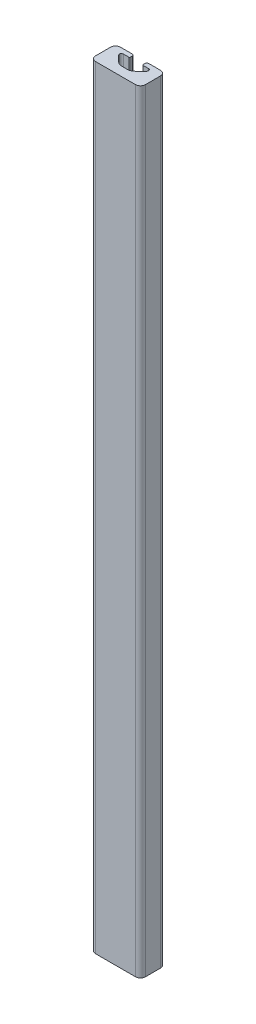
SolidWorks part; units mm, degrees
ref_plane "Alzado" through (0, 0, 0) normal (0, 0, 1) x (1, 0, 0)
ref_plane "Planta" through (0, 0, 0) normal (0, 1, 0) x (1, 0, 0)
ref_plane "Vista lateral" through (0, 0, 0) normal (1, 0, 0) x (0, 0, -1)
sketch "Croquis1" plane through (0, 0, 0) normal (0, 1, 0) x (1, 0, 0)
  line L0 (4.625, 10) -> (0, 10)
  line L1 (-2, 8) -> (-2, 2)
  line L2 (0, 0) -> (16, 0)
  line L3 (18, 2) -> (18, 8)
  line L4 (16, 10) -> (11.375, 10)
  line L5 (10.575, 9.2) -> (10.575, 8.5)
  line L6 (10.875, 8.2) -> (13.0441, 8.2)
  line L7 (13.5957, 6.8685) -> (11.2559, 4.5287)
  line L8 (9.1346, 3.65) -> (6.8654, 3.65)
  line L9 (4.7441, 4.5287) -> (2.4043, 6.8685)
  line L10 (2.9559, 8.2) -> (5.125, 8.2)
  line L11 (5.425, 8.5) -> (5.425, 9.2)
  arc A0 (0, 10) -> (-2, 8) centre (0, 8) ccw
  arc A1 (-2, 2) -> (0, 0) centre (0, 2) ccw
  arc A2 (16, 0) -> (18, 2) centre (16, 2) ccw
  arc A3 (18, 8) -> (16, 10) centre (16, 8) ccw
  arc A4 (11.375, 10) -> (10.575, 9.2) centre (11.375, 9.2) ccw
  arc A5 (10.575, 8.5) -> (10.875, 8.2) centre (10.875, 8.5) ccw
  arc A6 (13.5957, 6.8685) -> (13.0441, 8.2) centre (13.0441, 7.42) ccw
  arc A7 (9.1346, 3.65) -> (11.2559, 4.5287) centre (9.1346, 6.65) ccw
  arc A8 (4.7441, 4.5287) -> (6.8654, 3.65) centre (6.8654, 6.65) ccw
  arc A9 (2.9559, 8.2) -> (2.4043, 6.8685) centre (2.9559, 7.42) ccw
  arc A10 (5.125, 8.2) -> (5.425, 8.5) centre (5.125, 8.5) ccw
  arc A11 (5.425, 9.2) -> (4.625, 10) centre (4.625, 9.2) ccw
extrude "Saliente-Extruir1" add sketch "Croquis1" along normal blind 310
